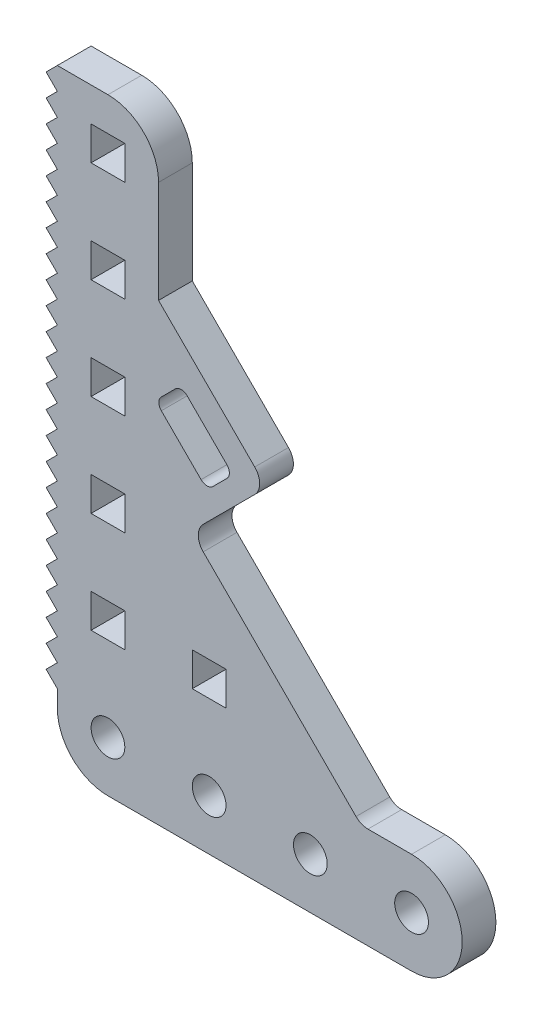
SolidWorks part; units mm, degrees
ref_plane "Alzado" through (0, 0, 0) normal (0, 0, 1) x (1, 0, 0)
ref_plane "Planta" through (0, 0, 0) normal (0, 1, 0) x (1, 0, 0)
ref_plane "Vista lateral" through (0, 0, 0) normal (1, 0, 0) x (0, 0, -1)
sketch "Model" plane through (0, 0, 0) normal (0, 0, 1) x (1, 0, 0)
  line L0 (20.9791, 285.5035) -> (19.9791, 286.5035)
  line L1 (19.9791, 286.5035) -> (20.9791, 287.5035)
  line L2 (20.9791, 283.5035) -> (19.9791, 284.5035)
  line L3 (19.9791, 284.5035) -> (20.9791, 285.5035)
  line L4 (20.9791, 281.5035) -> (19.9791, 282.5035)
  line L5 (19.9791, 282.5035) -> (20.9791, 283.5035)
  line L6 (20.9791, 279.5035) -> (19.9791, 280.5035)
  line L7 (19.9791, 280.5035) -> (20.9791, 281.5035)
  line L8 (20.9791, 277.5035) -> (19.9791, 278.5035)
  line L9 (19.9791, 278.5035) -> (20.9791, 279.5035)
  line L10 (20.9791, 275.5035) -> (19.9791, 276.5035)
  line L11 (19.9791, 276.5035) -> (20.9791, 277.5035)
  line L12 (20.9791, 273.5035) -> (19.9791, 274.5035)
  line L13 (19.9791, 274.5035) -> (20.9791, 275.5035)
  line L14 (20.9791, 271.5035) -> (19.9791, 272.5035)
  line L15 (19.9791, 272.5035) -> (20.9791, 273.5035)
  line L16 (20.9791, 269.5035) -> (19.9791, 270.5035)
  line L17 (19.9791, 270.5035) -> (20.9791, 271.5035)
  line L18 (20.9791, 267.5035) -> (19.9791, 268.5035)
  line L19 (19.9791, 268.5035) -> (20.9791, 269.5035)
  line L20 (20.9791, 265.5035) -> (19.9791, 266.5035)
  line L21 (19.9791, 266.5035) -> (20.9791, 267.5035)
  line L22 (20.9791, 263.5035) -> (19.9791, 264.5035)
  line L23 (19.9791, 264.5035) -> (20.9791, 265.5035)
  line L24 (20.9791, 261.5035) -> (19.9791, 262.5035)
  line L25 (19.9791, 262.5035) -> (20.9791, 263.5035)
  line L26 (20.9791, 259.5035) -> (19.9791, 260.5035)
  line L27 (19.9791, 260.5035) -> (20.9791, 261.5035)
  line L28 (20.9791, 257.5035) -> (19.9791, 258.5035)
  line L29 (19.9791, 258.5035) -> (20.9791, 259.5035)
  line L30 (20.9791, 255.5035) -> (19.9791, 256.5035)
  line L31 (19.9791, 256.5035) -> (20.9791, 257.5035)
  line L32 (20.9791, 253.5035) -> (19.9791, 254.5035)
  line L33 (19.9791, 254.5035) -> (20.9791, 255.5035)
  line L34 (20.9791, 251.5035) -> (19.9791, 252.5035)
  line L35 (19.9791, 252.5035) -> (20.9791, 253.5035)
  line L36 (20.9791, 249.5035) -> (19.9791, 250.5035)
  line L37 (19.9791, 250.5035) -> (20.9791, 251.5035)
  line L38 (20.9791, 247.5035) -> (19.9791, 248.5035)
  line L39 (19.9791, 248.5035) -> (20.9791, 249.5035)
  line L40 (20.9791, 245.5035) -> (19.9791, 246.5035)
  line L41 (19.9791, 246.5035) -> (20.9791, 247.5035)
  line L42 (20.9791, 243.5035) -> (19.9791, 244.5035)
  line L43 (19.9791, 244.5035) -> (20.9791, 245.5035)
  line L44 (20.9791, 241.5035) -> (19.9791, 242.5035)
  line L45 (19.9791, 242.5035) -> (20.9791, 243.5035)
  line L46 (20.9791, 239.5035) -> (19.9791, 240.5035)
  line L47 (19.9791, 240.5035) -> (20.9791, 241.5035)
  line L48 (23.9791, 284.5035) -> (23.9791, 281.5035)
  line L49 (26.9791, 284.5035) -> (23.9791, 284.5035)
  line L50 (26.9791, 281.5035) -> (26.9791, 284.5035)
  line L51 (23.9791, 281.5035) -> (26.9791, 281.5035)
  line L52 (23.9791, 248.5035) -> (23.9791, 245.5035)
  line L53 (26.9791, 248.5035) -> (23.9791, 248.5035)
  line L54 (26.9791, 245.5035) -> (26.9791, 248.5035)
  line L55 (23.9791, 245.5035) -> (26.9791, 245.5035)
  line L56 (23.9791, 275.5035) -> (23.9791, 272.5035)
  line L57 (26.9791, 275.5035) -> (23.9791, 275.5035)
  line L58 (26.9791, 272.5035) -> (26.9791, 275.5035)
  line L59 (23.9791, 272.5035) -> (26.9791, 272.5035)
  line L60 (23.9791, 257.5035) -> (23.9791, 254.5035)
  line L61 (26.9791, 257.5035) -> (23.9791, 257.5035)
  line L62 (26.9791, 254.5035) -> (26.9791, 257.5035)
  line L63 (23.9791, 254.5035) -> (26.9791, 254.5035)
  line L64 (23.9791, 266.5035) -> (23.9791, 263.5035)
  line L65 (26.9791, 266.5035) -> (23.9791, 266.5035)
  line L66 (26.9791, 263.5035) -> (26.9791, 266.5035)
  line L67 (23.9791, 263.5035) -> (26.9791, 263.5035)
  line L68 (32.9791, 248.5035) -> (32.9791, 245.5035)
  line L69 (35.9791, 248.5035) -> (32.9791, 248.5035)
  line L70 (35.9791, 245.5035) -> (35.9791, 248.5035)
  line L71 (32.9791, 245.5035) -> (35.9791, 245.5035)
  line L72 (38.5324, 263.2357) -> (33.9503, 258.6536)
  line L73 (29.9791, 273.9104) -> (38.5324, 265.3571)
  line L74 (36.0575, 263.2357) -> (34.8201, 261.9983)
  line L75 (32.522, 267.8319) -> (36.0575, 264.2964)
  line L76 (30.2239, 266.5945) -> (31.4613, 267.8319)
  line L77 (33.7594, 261.9983) -> (30.2239, 265.5338)
  line L78 (20.9791, 238.0035) -> (20.9791, 239.5035)
  line L79 (25.4791, 287.5035) -> (20.9791, 287.5035)
  line L80 (47.5398, 242.9429) -> (33.9503, 256.5323)
  line L81 (29.9791, 273.9104) -> (29.9791, 283.0035)
  line L82 (52.4791, 242.5035) -> (48.6004, 242.5035)
  line L83 (25.4791, 233.5035) -> (52.4791, 233.5035)
  arc A0 (33.9503, 258.6536) -> (33.9503, 256.5323) centre (35.011, 257.593) ccw
  arc A1 (38.5324, 263.2357) -> (38.5324, 265.3571) centre (37.4717, 264.2964) ccw
  arc A2 (33.7594, 261.9983) -> (34.8201, 261.9983) centre (34.2898, 262.5286) ccw
  arc A3 (36.0575, 263.2357) -> (36.0575, 264.2964) centre (35.5272, 263.7661) ccw
  arc A4 (32.522, 267.8319) -> (31.4613, 267.8319) centre (31.9917, 267.3016) ccw
  arc A5 (30.2239, 266.5945) -> (30.2239, 265.5338) centre (30.7542, 266.0642) ccw
  circle A6 centre (43.4791, 238.0035) radius 1.5
  circle A7 centre (34.4791, 238.0035) radius 1.5
  arc A8 (47.5398, 242.9429) -> (48.6004, 242.5035) centre (48.6004, 244.0035) ccw
  arc A9 (29.9791, 283.0035) -> (25.4791, 287.5035) centre (25.4791, 283.0035) ccw
  circle A10 centre (52.4791, 238.0035) radius 1.5
  arc A11 (52.4791, 233.5035) -> (52.4791, 242.5035) centre (52.4791, 238.0035) ccw
  arc A12 (20.9791, 238.0035) -> (25.4791, 233.5035) centre (25.4791, 238.0035) ccw
  circle A13 centre (25.4791, 238.0035) radius 1.5
extrude "Saliente-Extruir1" add sketch "Model" along normal blind 3
